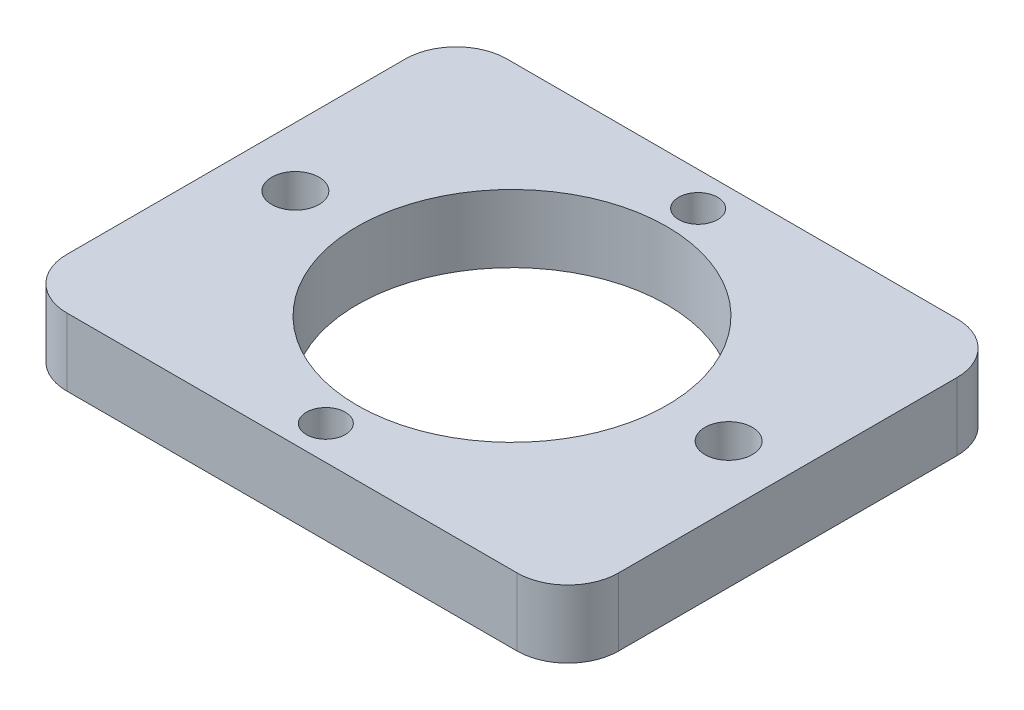
SolidWorks part; units mm, degrees
ref_plane "Front" through (0, 0, 0) normal (0, 0, 1) x (1, 0, 0)
ref_plane "Top" through (0, 0, 0) normal (0, 1, 0) x (1, 0, 0)
ref_plane "Right" through (0, 0, 0) normal (1, 0, 0) x (0, 0, -1)
sketch "Sketch1" plane through (0, 0, 0) normal (0, 1, 0) x (1, 0, 0)
  line L1 (0, 0) -> (32.6, 0)
  line L2 (0, 0) -> (0, -26)
  line L3 (0, -26) -> (32.6, -26)
  line L4 (32.6, 0) -> (32.6, -26)
  dimension "D1" = 26
  dimension "D2" = 32.6
extrude "Boss-Extrude1" add sketch "Sketch1" along normal blind 4
sketch "Sketch2" plane through (0, 4, 0) normal (0, 1, 0) x (1, 0, 0)
  line L0 (0, 0) -> (0, -26) construction
  line L1 (32.6, -26) -> (32.6, 0) construction
  line L2 (32.6, 0) -> (0, 0) construction
  line L3 (0, -26) -> (32.6, -26) construction
  circle A0 centre (16.3, -13) radius 9.15
  circle A1 centre (3.5, -13) radius 1.4
  circle A2 centre (29.1, -13) radius 1.4
  circle A3 centre (16.3, -2) radius 1.15
  circle A4 centre (16.3, -24) radius 1.15
  dimension "D1" = 18.3
  dimension "D2" = 2.8
  dimension "D3" = 2.8
  dimension "D4" = 2.3
  dimension "D5" = 2.3
  dimension "D6" = 3.5
  dimension "D7" = 3.5
  dimension "D8" = 2
  dimension "D9" = 2
extrude "Cut-Extrude1" cut sketch "Sketch2" against normal blind 4
fillet "Fillet1" radius 3 4 edges at (32.6, 2, 26) (0, 2, 26) (32.6, 2, 0) (0, 2, 0)
equation "\"滑动-垂直孔\" = 0.6"
equation "\"滑动-水平孔\"= 0.3"
equation "\"松动-垂直孔\" = 0.3"
equation "\"松动-水平孔\"= 0.1"
equation "\"正常-垂直孔\" = 0.15"
equation "\"正常-水平孔\"= 0"
equation "\"紧缩-垂直孔\"= 0"
equation "\"紧缩-水平孔\"= - 0.1"
equation "\"D4@Sketch2\"=\"松动-垂直孔\"+2"
equation "\"D5@Sketch2\"=\"松动-垂直孔\"+2"
equation "\"D2@Sketch2\"=\"松动-垂直孔\"+2.5"
equation "\"D3@Sketch2\"=\"松动-垂直孔\"+2.5"
equation "\"D1@Sketch2\"=\"松动-垂直孔\"+18mm"
